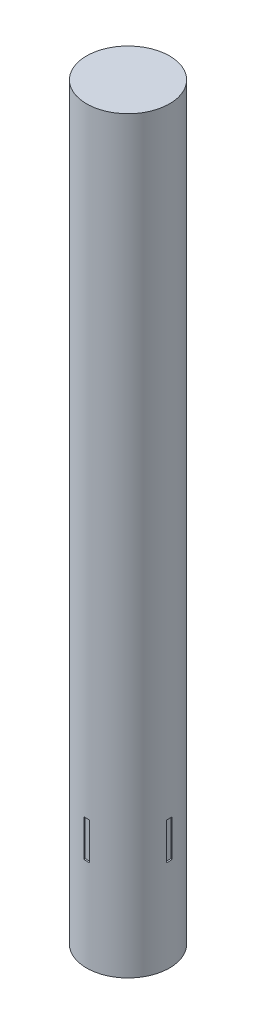
SolidWorks part; units mm, degrees
other "Stage 1"
ref_plane "Front Plane" through (0, 0, 0) normal (0, 0, 1) x (1, 0, 0)
ref_plane "Top Plane" through (0, 0, 0) normal (0, 1, 0) x (1, 0, 0)
ref_plane "Right Plane" through (0, 0, 0) normal (1, 0, 0) x (0, 0, -1)
sketch "Sketch1" plane through (0, 0, 0) normal (0, 0, 1) x (1, 0, 0)
  line L0 (2023.7498, 0) -> (-2023.7498, 0) construction
  line L1 (0, -2406.2532) -> (0, 2406.2532) construction
  line L3 (0, 0) -> (112, 0)
  line L4 (0, 0) -> (0, -2020)
  line L5 (0, -2020) -> (112, -2020)
  line L6 (112, 0) -> (112, -2020)
  point P4 (0, 0)
  point P8 (0, 0)
  dimension "D1" = 2020
  dimension "D2" = 112
revolve "Revolve1" add sketch "Sketch1" angle 360 about L1
sketch "Sketch2" plane through (0, 0, 0) normal (0, 0, 1) x (1, 0, 0)
  line L0 (-112, -2020) -> (112, -2020) construction
  line L1 (-7.5, -1770) -> (7.5, -1770)
  line L2 (-7.5, -1770) -> (-7.5, -1670)
  line L3 (-7.5, -1670) -> (7.5, -1670)
  line L4 (7.5, -1770) -> (7.5, -1670)
  line L5 (-7.5, -1770) -> (7.5, -1670) construction
  line L6 (-7.5, -1670) -> (7.5, -1770) construction
  point P0 (0, -1720)
  dimension "D1" = 100
  dimension "D2" = 15
  dimension "D3" = 0
  dimension "D4" = 300
extrude "Cut-Extrude1" cut sketch "Sketch2" against normal blind 132
sketch "Sketch3" plane through (0, 0, 0) normal (0, 0, -1) x (-1, 0, 0)
  line L8 (-7.5, -1670) -> (-7.5, -1770)
  line L9 (-7.5, -1770) -> (7.5, -1770)
  line L10 (7.5, -1770) -> (7.5, -1670)
  line L11 (7.5, -1670) -> (-7.5, -1670)
  line L12 (-7.5, -1670) -> (-7.5, -1770)
  line L13 (-7.5, -1770) -> (7.5, -1770)
  line L14 (7.5, -1770) -> (7.5, -1670)
  line L15 (7.5, -1670) -> (-7.5, -1670)
  dimension "D1" = 0
extrude "Boss-Extrude1" add sketch "Sketch3" along normal blind 108
pattern_circular "CirPattern1" count 4 over 360 about axis through (0, 0, 0) along (0, 1, 0) of "Cut-Extrude1", "Boss-Extrude1"
sketch "Sketch4" plane through (0, -2020, 0) normal (0, -1, 0) x (1, 0, 0)
  circle A0 centre (0, 0) radius 107
  dimension "D1" = 214
extrude "Cut-Extrude2" cut sketch "Sketch4" against normal blind 200
